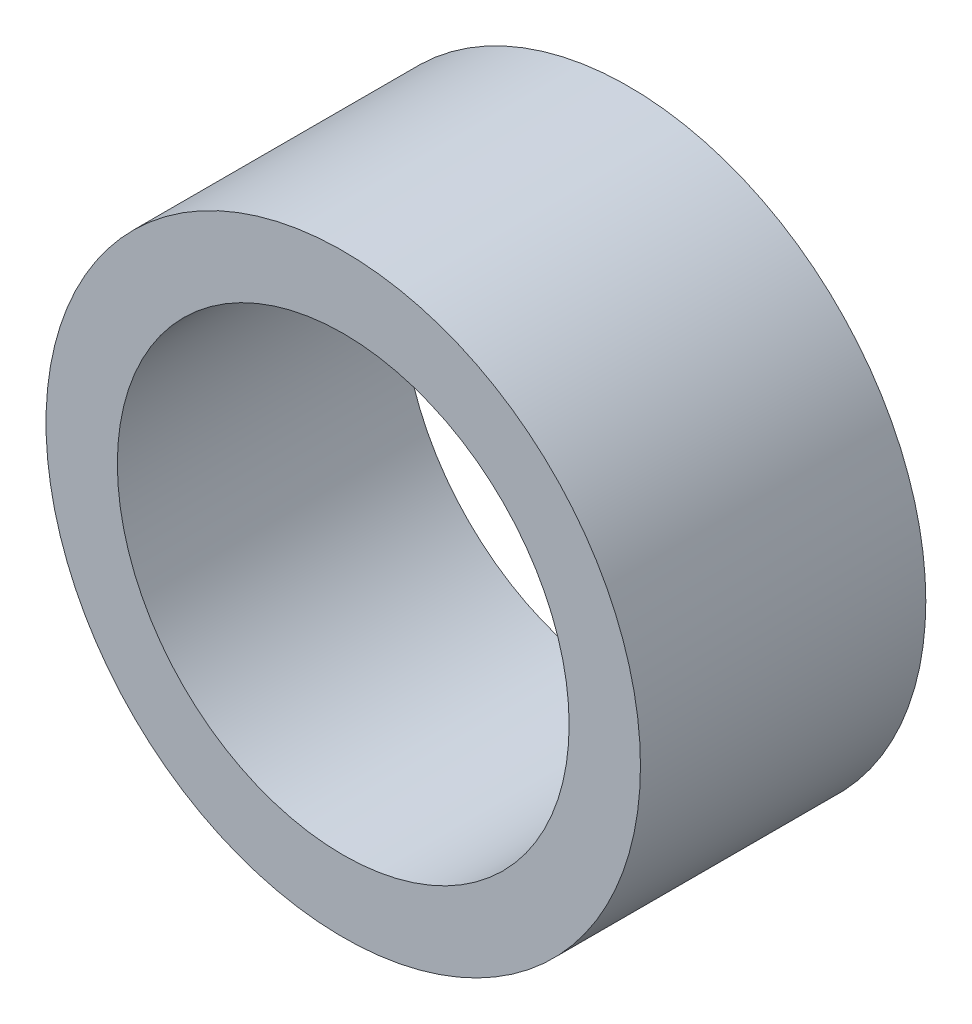
SolidWorks part; units mm, degrees
ref_plane "正面" through (0, 0, 0) normal (0, 0, 1) x (1, 0, 0)
ref_plane "平面" through (0, 0, 0) normal (0, 1, 0) x (1, 0, 0)
ref_plane "右側面" through (0, 0, 0) normal (1, 0, 0) x (0, 0, -1)
sketch "ｽｹｯﾁ1" plane through (0, 0, 0) normal (0, 0, 1) x (1, 0, 0)
  circle A0 centre (0, 0) radius 2.5
  circle A1 centre (0, 0) radius 1.9
  dimension "D1" = 5
  dimension "D2" = 3.8
extrude "ﾎﾞｽ - 押し出し1" add sketch "ｽｹｯﾁ1" along normal blind 2.4
